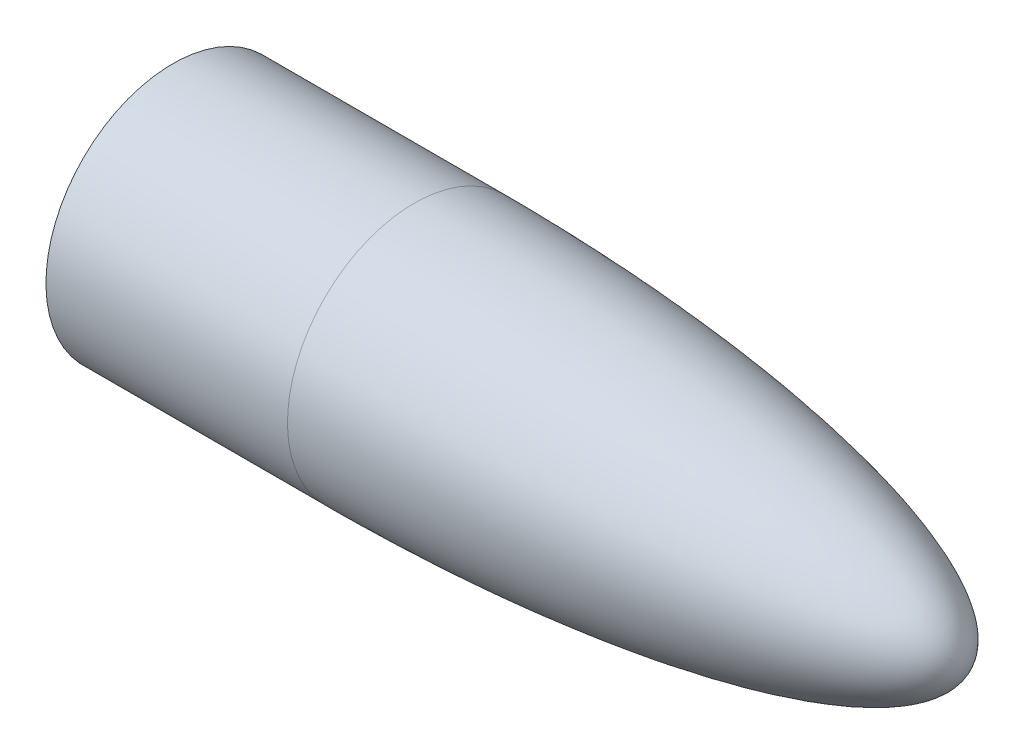
SolidWorks part; units mm, degrees
ref_plane "Front Plane" through (0, 0, 0) normal (0, 0, 1) x (1, 0, 0)
ref_plane "Top Plane" through (0, 0, 0) normal (0, 1, 0) x (1, 0, 0)
ref_plane "Right Plane" through (0, 0, 0) normal (1, 0, 0) x (0, 0, -1)
sketch "Sketch1" plane through (0, 0, 0) normal (0, 0, 1) x (1, 0, 0)
  line L0 (-36.6063, 0) -> (114, 0) construction
  line L5 (114, 0) -> (115.27, 0)
  line L6 (115.27, 0.022) -> (115.27, 0)
  line L7 (0, 25.4) -> (-50.8, 25.4)
  line L8 (-50.8, 25.4) -> (-50.8, 26.67)
  line L9 (-50.8, 26.67) -> (0, 26.67)
  spline S0 degree 4 poles (-11.4201, 25.2727) (-10.6168, 25.2886) (-9.4027, 25.3179) (-6.9196, 25.3537) (-4.521, 25.3854) (-1.2795, 25.4004) (0.6759, 25.4015) (3.3383, 25.3917) (5.3351, 25.3735) (7.5809, 25.3462) (9.6855, 25.3097) (11.8715, 25.2641) (14.0116, 25.2092) (16.7146, 25.129) (19.9425, 25.0141) (23.7165, 24.8524) (28.0223, 24.6289) (32.3288, 24.3658) (36.6309, 24.0619) (40.9308, 23.7156) (45.2263, 23.3253) (50.5906, 22.7798) (55.9461, 22.1534) (61.2906, 21.4387) (67.6868, 20.4624) (72.9999, 19.5413) (78.2902, 18.4967) (84.6006, 17.0651) (90.3027, 15.5736) (95.9329, 13.8205) (101.2174, 11.7655) (104.9646, 9.9748) (107.604, 8.4452) (109.5234, 7.0963) (110.8835, 5.9396) (111.8523, 4.9439) (112.5623, 4.0571) (113.0812, 3.2569) (113.4609, 2.5113) (113.7264, 1.8109) (113.9103, 1.1036) (113.9824, 0.5693) (114, 0.2064) (114, 0) knots 0 0 0 0 0 0.021551 0.043102 0.064653 0.086204 0.102511 0.118818 0.135125 0.151432 0.167739 0.184046 0.200353 0.21666 0.249275 0.281889 0.314503 0.347117 0.379731 0.412345 0.444959 0.477573 0.542801 0.575415 0.60803 0.673258 0.705872 0.738486 0.803714 0.851476 0.88409 0.909828 0.929204 0.943632 0.95495 0.96375 0.971158 0.977939 0.983743 0.98901 0.993768 1 1 1 1 1 construction
  spline S1 degree 4 poles (0, 25.4) (0.4927, 25.4) (1.4901, 25.3985) (3.3383, 25.3917) (5.3351, 25.3735) (7.5809, 25.3462) (9.6855, 25.3097) (11.8715, 25.2641) (14.0116, 25.2092) (16.7146, 25.129) (19.9425, 25.0141) (23.7165, 24.8524) (28.0223, 24.6289) (32.3288, 24.3658) (36.6309, 24.0619) (40.9308, 23.7156) (45.2263, 23.3253) (50.5906, 22.7798) (55.9461, 22.1534) (61.2906, 21.4387) (67.6868, 20.4624) (72.9999, 19.5413) (78.2902, 18.4967) (84.6006, 17.0651) (90.3027, 15.5736) (95.9329, 13.8205) (101.2174, 11.7655) (104.9646, 9.9748) (107.604, 8.4452) (109.5234, 7.0963) (110.8835, 5.9396) (111.8523, 4.9439) (112.5623, 4.0571) (113.0812, 3.2569) (113.4609, 2.5113) (113.7264, 1.8109) (113.9103, 1.1036) (113.9824, 0.5693) (114, 0.2064) (114, 0) knots 0.086204 0.086204 0.086204 0.086204 0.086204 0.102511 0.118818 0.135125 0.151432 0.167739 0.184046 0.200353 0.21666 0.249275 0.281889 0.314503 0.347117 0.379731 0.412345 0.444959 0.477573 0.542801 0.575415 0.60803 0.673258 0.705872 0.738486 0.803714 0.851476 0.88409 0.909828 0.929204 0.943632 0.95495 0.96375 0.971158 0.977939 0.983743 0.98901 0.993768 1 1 1 1 1
  spline S2 degree 1 poles (0, 26.67) (115.27, 0.0002) knots 0 0 1 1 construction
  spline S3 degree 3 poles (0, 26.67) (0.2954, 26.67) (0.869, 26.6694) (1.8319, 26.6668) (2.8403, 26.6624) (4.1369, 26.6543) (5.6474, 26.6397) (7.5887, 26.6152) (9.4581, 26.5837) (11.9916, 26.5323) (16.3995, 26.4175) (22.7121, 26.1819) (32.794, 25.6474) (45.3848, 24.6708) (57.9365, 23.2253) (67.938, 21.7187) (75.4116, 20.3846) (82.8465, 18.8062) (90.2239, 16.9197) (96.297, 15.0056) (101.0723, 13.1652) (104.592, 11.5818) (108.013, 9.7184) (110.7228, 7.8191) (112.6952, 5.9426) (114.0036, 4.2864) (114.9969, 2.3178) (115.2675, 0.7846) (115.27, 0.0147) (115.27, 0.0056) (115.27, 0.0002) knots 0.086204 0.086204 0.086204 0.086204 0.093343 0.100482 0.107621 0.11476 0.129038 0.143316 0.157594 0.171872 0.200429 0.257541 0.314653 0.428878 0.543102 0.600214 0.657327 0.714439 0.771551 0.828663 0.857219 0.885776 0.914332 0.942888 0.957166 0.971444 0.985722 0.999832 0.999899 1 1 1 1 only from (0, 26.67) to (115.27, 0.022)
  dimension "D2" = 50.8
  dimension "D3" = 1.27
  dimension "D1" = 1.27
revolve "Revolve1" add sketch "Sketch1" angle 360 about L0
